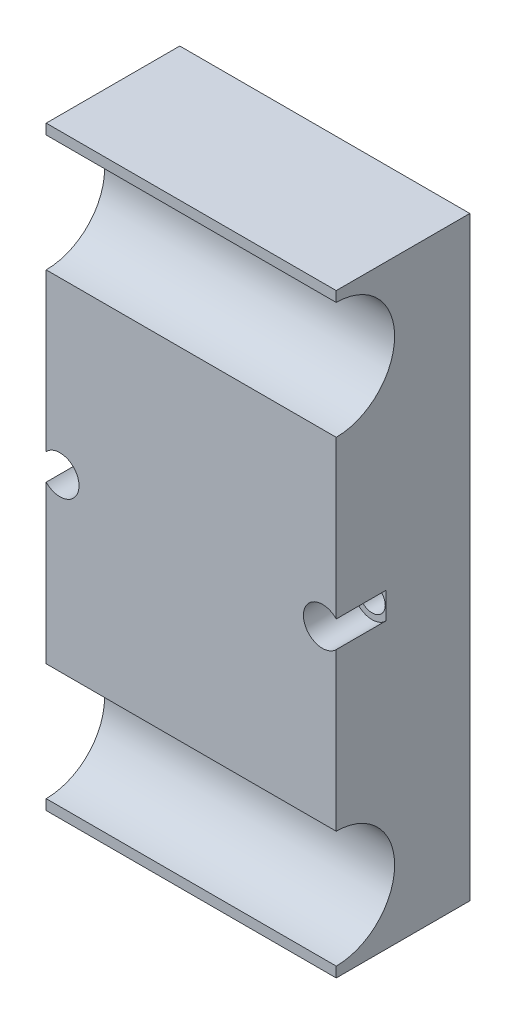
SolidWorks part; units mm, degrees
ref_plane "Front Plane" through (0, 0, 0) normal (0, 0, 1) x (1, 0, 0)
ref_plane "Top Plane" through (0, 0, 0) normal (0, 1, 0) x (1, 0, 0)
ref_plane "Right Plane" through (0, 0, 0) normal (1, 0, 0) x (0, 0, -1)
sketch "Sketch1" plane through (0, 0, 0) normal (0, 0, 1) x (1, 0, 0)
  line L1 (0, 0) -> (38, 0)
  line L2 (0, 0) -> (0, 78)
  line L3 (0, 78) -> (38, 78)
  line L4 (38, 0) -> (38, 78)
  dimension "D1" = 78
  dimension "D2" = 38
extrude "Boss-Extrude1" add sketch "Sketch1" along normal blind 10
sketch "Sketch2" plane through (0, 0, 0) normal (0, 0, -1) x (-1, 0, 0)
  line L0 (0, 78) -> (0, 0) construction
  line L1 (-34.25, 3.75) -> (-3.75, 3.75)
  line L2 (-34.25, 3.75) -> (-34.25, 74.25)
  line L3 (-34.25, 74.25) -> (-3.75, 74.25)
  line L4 (-3.75, 3.75) -> (-3.75, 74.25)
  line L7 (-38, 78) -> (0, 78) construction
  dimension "D1" = 70.5
  dimension "D2" = 30.5
  dimension "D3" = 3.75
  dimension "D4" = 3.75
extrude "Cut-Extrude1" cut sketch "Sketch2" against normal blind 8
sketch "Sketch3" plane through (0, 0, 8) normal (0, 0, -1) x (-1, 0, 0)
  line L0 (-30.25, 74.25) -> (-34.25, 70.25)
  line L1 (-3.75, 74.25) -> (-34.25, 74.25) construction
  line L2 (-34.25, 74.25) -> (-34.25, 3.75) construction
  line L3 (-34.25, 70.25) -> (-34.25, 74.25)
  line L4 (-34.25, 74.25) -> (-30.25, 74.25)
  line L5 (-19, 74.25) -> (-19, 3.75) construction
  line L6 (-34.25, 3.75) -> (-3.75, 3.75) construction
  line L7 (-34.25, 39) -> (-3.75, 39) construction
  line L8 (-3.75, 3.75) -> (-3.75, 74.25) construction
  line L9 (-3.75, 70.25) -> (-3.75, 74.25)
  line L10 (-3.75, 74.25) -> (-7.75, 74.25)
  line L11 (-7.75, 74.25) -> (-3.75, 70.25)
  line L12 (-3.75, 7.75) -> (-3.75, 3.75)
  line L13 (-3.75, 3.75) -> (-7.75, 3.75)
  line L14 (-7.75, 3.75) -> (-3.75, 7.75)
  line L15 (-34.25, 7.75) -> (-34.25, 3.75)
  line L16 (-34.25, 3.75) -> (-30.25, 3.75)
  line L17 (-30.25, 3.75) -> (-34.25, 7.75)
  dimension "D1" = 4
  dimension "D2" = 4
extrude "Boss-Extrude2" add sketch "Sketch3" along normal blind 4
sketch "Sketch4" plane through (0, 0, 10) normal (0, 0, 1) x (1, 0, 0)
  line L1 (0, 78) -> (38, 78)
  line L2 (0, 78) -> (0, 0)
  line L3 (0, 0) -> (38, 0)
  line L4 (38, 78) -> (38, 0)
extrude "Boss-Extrude3" add sketch "Sketch4" along normal blind 7.5
sketch "Sketch5" plane through (38, 0, 0) normal (1, 0, 0) x (0, 0, -1)
  line L0 (-17.5, 0) -> (-17.5, 78) construction
  line L3 (-17.5, 0) -> (0, 0) construction
  circle A0 centre (-17.5, 9) radius 7.65
  circle A1 centre (-17.5, 69) radius 7.65
  point P8 (-11.167, 16.6525)
  dimension "D1" = 60
  dimension "D2" = 9
  dimension "D3" = 15.3
  dimension "D4" = 15.3
extrude "Cut-Extrude2" cut sketch "Sketch5" against normal through all
sketch "Sketch6" plane through (0, 0, 0) normal (0, 0, -1) x (-1, 0, 0)
  line L1 (-34.25, 74.25) -> (-3.75, 74.25)
  line L2 (-34.25, 74.25) -> (-34.25, 3.75)
  line L3 (-34.25, 3.75) -> (-3.75, 3.75)
  line L4 (-3.75, 74.25) -> (-3.75, 3.75)
  line L5 (-36.25, 76.25) -> (-1.75, 76.25)
  line L6 (-36.25, 76.25) -> (-36.25, 1.75)
  line L7 (-36.25, 1.75) -> (-1.75, 1.75)
  line L8 (-1.75, 76.25) -> (-1.75, 1.75)
  dimension "D1" = 2
  dimension "D2" = 2
  dimension "D3" = 2
  dimension "D4" = 2
extrude "Cut-Extrude3" cut sketch "Sketch6" against normal blind 1
sketch "Sketch7" plane through (0, 0, 17.5) normal (0, 0, 1) x (1, 0, 0)
  line L0 (0, 39) -> (38, 39) construction
  line L1 (0, 61.35) -> (0, 16.65) construction
  line L2 (38, 16.65) -> (38, 61.35) construction
  circle A0 centre (1.8, 39) radius 1.725
  circle A1 centre (36.2, 39) radius 1.725
  dimension "D1" = 1.8
  dimension "D2" = 3.45
  dimension "D3" = 1.8
extrude "Cut-Extrude5" cut sketch "Sketch7" against normal through all
sketch "Sketch8" plane through (0, 0, 17.5) normal (0, 0, 1) x (1, 0, 0)
  circle A0 centre (1.8, 39) radius 2.5
  circle A1 centre (36.2, 39) radius 2.5
  dimension "D1" = 5
extrude "Cut-Extrude6" cut sketch "Sketch8" against normal blind 6.5
